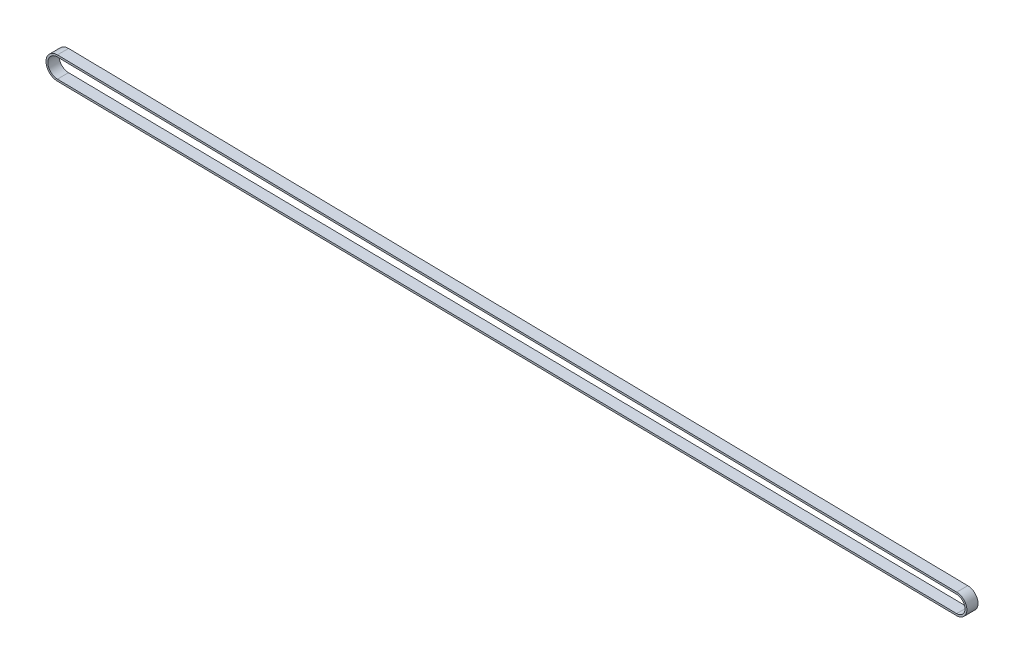
SolidWorks part; units mm, degrees
ref_plane "Front Plane" through (0, 0, 0) normal (0, 0, 1) x (1, 0, 0)
ref_plane "Top Plane" through (0, 0, 0) normal (0, 1, 0) x (1, 0, 0)
ref_plane "Right Plane" through (0, 0, 0) normal (1, 0, 0) x (0, 0, -1)
sketch "Sketch1" plane through (0, 0, 0) normal (0, 0, 1) x (1, 0, 0)
  line L0 (0, 5.15) -> (483.9263, -3.297)
  line L1 (0, 5.15) -> (0, -5.15) construction
  line L2 (483.9263, -3.297) -> (483.9263, -12.297) construction
  line L3 (483.9263, -12.297) -> (0, -5.15)
  line L4 (483.9263, -2.297) -> (0, 6.15)
  line L5 (0, -6.15) -> (483.9263, -13.297)
  arc A0 (0.1797, 5.1469) -> (0, -5.15) centre (0, 0) ccw
  arc A1 (483.9263, -12.297) -> (483.9263, -3.297) centre (483.9263, -7.797) ccw
  arc A2 (0.2146, 6.1463) -> (0, -6.15) centre (0, 0) ccw
  arc A3 (483.7639, -13.2946) -> (483.9263, -2.297) centre (483.9263, -7.797) ccw
  dimension "D1" = 10.3
  dimension "D5" = 12.3
  dimension "D6" = 11
  dimension "D2" = 484
  dimension "D3" = 89
  dimension "D4" = 9
extrude "Boss-Extrude1" add sketch "Sketch1" along normal blind 6 contours L5 A3 L4 A2 A1 L3 A0 L0
